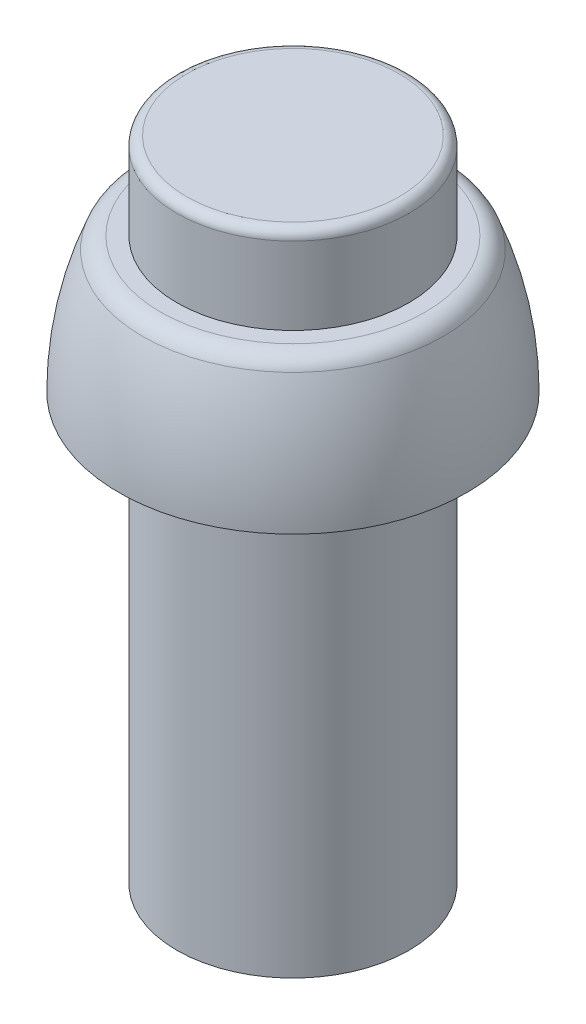
SolidWorks part; units mm, degrees
ref_plane "Alzado" through (0, 0, 0) normal (0, 0, 1) x (1, 0, 0)
ref_plane "Planta" through (0, 0, 0) normal (0, 1, 0) x (1, 0, 0)
ref_plane "Vista lateral" through (0, 0, 0) normal (1, 0, 0) x (0, 0, -1)
sketch "Croquis1" plane through (0, 0, 0) normal (0, 1, 0) x (1, 0, 0)
  circle A0 centre (0, 0) radius 6
  dimension "D1" = 12
extrude "Saliente-Extruir1" add sketch "Croquis1" against normal blind 22
sketch "Croquis2" plane through (0, 0, 0) normal (1, 0, 0) x (0, 0, -1)
  line L1 (6, 0) -> (-6, 0) construction
  line L2 (0, 0) -> (9, 0)
  line L8 (0, 0) -> (0, 7)
  line L9 (0, 7) -> (7.5, 7)
  arc A0 (9, 0) -> (7.5, 7) centre (-8.0833, 0) ccw
  dimension "D1" = 7
  dimension "D2" = 9
  dimension "D3" = 7.5
revolve "Revolución1" add sketch "Croquis2" angle 360 about L8
fillet "Redondeo2" radius 1 1 edges at (0, 7, -7.5)
sketch "Croquis3" plane through (0, 0, 0) normal (1, 0, 0) x (0, 0, -1)
  line L0 (0, 7) -> (0, 11.5)
  line L1 (6.8389, 7) -> (-6.8389, 7) construction
  line L2 (0, 11.5) -> (6, 11.5)
  line L3 (6, 11.5) -> (6, 7)
  line L4 (6, 7) -> (0, 7)
  dimension "D1" = 4.5
  dimension "D2" = 6
revolve "Revolución2" add sketch "Croquis3" angle 360 about L0
fillet "Redondeo3" radius 0.5 1 edges at (0, 11.5, -6)
